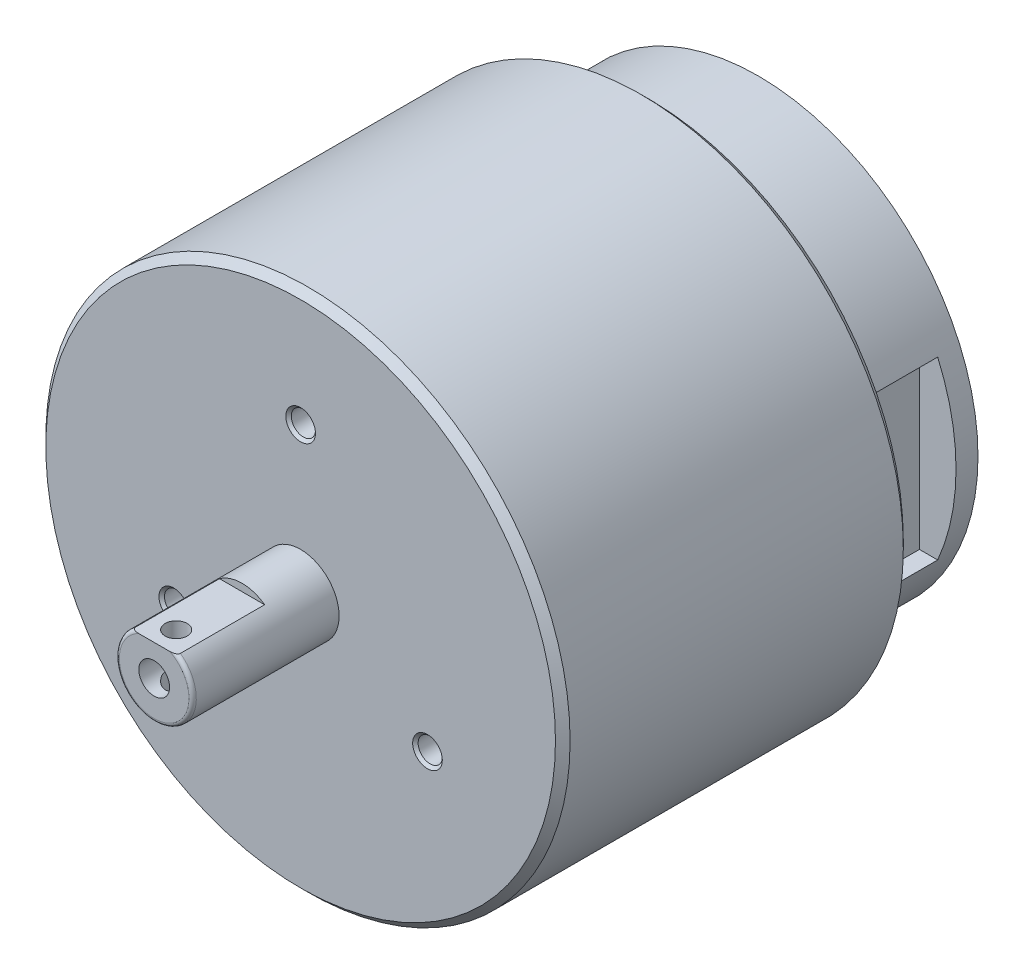
SolidWorks part; units mm, degrees
material "自定义塑料"
ref_plane "前视基准面" through (0, 0, 0) normal (0, 0, 1) x (1, 0, 0)
ref_plane "上视基准面" through (0, 0, 0) normal (0, 1, 0) x (1, 0, 0)
ref_plane "右视基准面" through (0, 0, 0) normal (1, 0, 0) x (0, 0, -1)
sketch "草图1" plane through (0, 0, 0) normal (0, 0, 1) x (1, 0, 0)
  circle A0 centre (0, 0) radius 35.8
  dimension "D1" = 71.6
extrude "凸台-拉伸1" add sketch "草图1" along normal blind 47.5
hole_wizard "M4 螺纹孔1" positions "草图6" profile "草图7" tap size "M4" standard "ISO"
sketch "草图6" plane through (0, 0, 47.5) normal (0, 0, 1) x (1, 0, 0)
  line L0 (0, 0) -> (0, 20) construction
  line L3 (0, 0) -> (17.3205, -10) construction
  line L6 (0, 0) -> (-17.3205, -10) construction
  point P0 (0, 20)
  point P2 (17.3205, -10)
  point P4 (-17.3205, -10)
  dimension "D1" = 20
  dimension "D2" = 120
sketch "草图7" plane through (0, 20, 47.5) normal (1, 0, 0) x (0, -1, 0)
  line L0 (0, 0) -> (0, 11.0914)
  line L1 (0, 11.0914) -> (1.65, 10.1)
  line L2 (1.65, 10.1) -> (1.65, 0.375)
  line L3 (1.65, 0.375) -> (2.025, 0)
  line L5 (2.025, 0) -> (0, 0)
  line L6 (-1.65, 0.375) -> (-2.025, 0) construction
  line L10 (0, 11.0914) -> (-1.65, 10.1) construction
  line L11 (0, -6.35) -> (0, 107.95) construction
  dimension "螺纹孔钻头直径" = 3.3
  dimension "螺纹孔钻头深度" = 10.1
  dimension "近端锥形沉头孔直径" = 4.05
  dimension "近端锥形沉头孔角度" = 90
  dimension "导头角度" = 118
cosmetic thread "孔螺蚊线1" parameters "D1"=8, "D2"=4
cosmetic thread "孔螺蚊线2" parameters "D1"=8, "D2"=4
cosmetic thread "孔螺蚊线3" parameters "D1"=8, "D2"=4
chamfer "倒角1" distance 1 angle 45 2 edges at (35.8, 0, 0) (35.8, 0, 47.5)
sketch "草图8" plane through (0, 0, 0) normal (0, 0, -1) x (-1, 0, 0)
  circle A0 centre (0, 0) radius 30
  dimension "D1" = 60
extrude "凸台-拉伸2" add sketch "草图8" along normal blind 16
sketch "草图9" plane through (0, 0, 47.5) normal (0, 0, 1) x (1, 0, 0)
  circle A0 centre (0, 0) radius 5.25
  dimension "D1" = 10.5
extrude "凸台-拉伸3" add sketch "草图9" along normal blind 20
fillet "圆角1" radius 0.5 1 edges at (5.25, 0, 67.5)
hole_wizard "M5 螺纹孔1" positions "草图11" profile "草图12" tap size "M5" standard "GB"
sketch "草图11" plane through (0, 0, 67.5) normal (0, 0, 1) x (1, 0, 0)
  point P0 (0, 0)
sketch "草图12" plane through (0, 0, 67.5) normal (1, 0, 0) x (0, -1, 0)
  line L0 (0, 0) -> (0, 13.6618)
  line L1 (0, 13.6618) -> (2.1, 12.4)
  line L2 (2.1, 12.4) -> (2.1, 0)
  line L5 (2.1, 0) -> (0, 0)
  line L10 (0, 13.6618) -> (-2.1, 12.4) construction
  line L11 (0, -6.35) -> (0, 107.95) construction
  dimension "螺纹孔钻头直径" = 4.2
  dimension "螺纹孔钻头深度" = 12.4
  dimension "导头角度" = 118
cosmetic thread "孔螺蚊线4" parameters "D1"=10, "D2"=5
sketch "草图13" plane through (0, 0, 67.5) normal (0, 0, 1) x (1, 0, 0)
  line L0 (-3.0822, 4.25) -> (3.0822, 4.25)
  circle A0 centre (0, 0) radius 5.25 construction
  arc A1 (3.0822, 4.25) -> (-3.0822, 4.25) centre (0, 0) ccw
  point P4 (0, 5.25)
  dimension "D1" = 1
extrude "切除-拉伸1" cut sketch "草图13" against normal blind 12
sketch "草图14" plane through (0, 4.25, 0) normal (0, 1, 0) x (1, 0, 0)
  line L0 (-4.75, -67.5) -> (4.75, -67.5) construction
  line L1 (-3.0822, -55.5) -> (3.0822, -55.5) construction
  circle A0 centre (0, -64.5) radius 1.5
  point P4 (0, 0)
  point P7 (0, -55.5)
  dimension "D1" = 3
  dimension "D2" = 3
extrude "切除-拉伸2" cut sketch "草图14" against normal through all
ref_plane "基准面1" through (30, 0, 0) normal (1, 0, 0) x (0, 0, -1)
sketch "草图15" plane through (30, 0, 0) normal (1, 0, 0) x (0, 0, -1)
  line L0 (0, -30) -> (0, 30) construction
  line L1 (0, 12) -> (12, 12)
  line L2 (0, 12) -> (0, -12)
  line L3 (0, -12) -> (12, -12)
  line L4 (12, 12) -> (12, -12)
  line L5 (16, -30) -> (16, 30) construction
  point P9 (0, 0)
  dimension "D1" = 4
  dimension "D2" = 24
extrude "切除-拉伸3" cut sketch "草图15" against normal blind 5
chamfer "倒角2" distance 1 distance2 3 1 edges at (-30, 0, -16)
